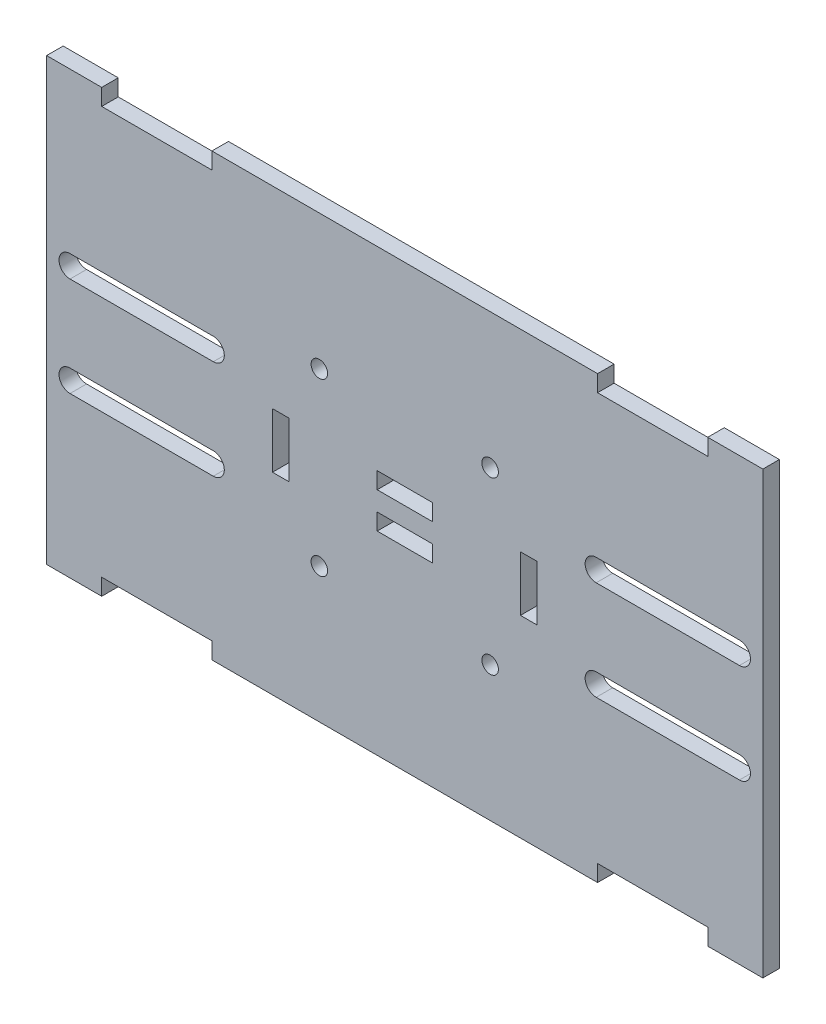
SolidWorks part; units mm, degrees
ref_plane "Front Plane" through (0, 0, 0) normal (0, 0, 1) x (1, 0, 0)
ref_plane "Top Plane" through (0, 0, 0) normal (0, 1, 0) x (1, 0, 0)
ref_plane "Right Plane" through (0, 0, 0) normal (1, 0, 0) x (0, 0, -1)
sketch "Sketch1" plane through (0, 0, 0) normal (0, 0, 1) x (1, 0, 0)
  line L0 (-55, 40) -> (-55, 37)
  line L1 (65, -40) -> (55, -40)
  line L2 (65, -40) -> (65, 40)
  line L3 (65, 40) -> (55, 40)
  line L4 (-65, -40) -> (-65, 40)
  line L5 (65, -40) -> (-65, 40) construction
  line L6 (65, 40) -> (-65, -40) construction
  line L7 (-55, 37) -> (-35, 37)
  line L8 (-35, 37) -> (-35, 40)
  line L9 (35, 40) -> (35, 37)
  line L10 (35, 37) -> (55, 37)
  line L11 (55, 37) -> (55, 40)
  line L12 (-55, -40) -> (-55, -37)
  line L13 (-55, -37) -> (-35, -37)
  line L14 (-35, -37) -> (-35, -40)
  line L15 (35, -40) -> (35, -37)
  line L16 (35, -37) -> (55, -37)
  line L17 (55, -37) -> (55, -40)
  line L18 (-55, 40) -> (-65, 40)
  line L19 (35, 40) -> (-35, 40)
  line L20 (35, -40) -> (-35, -40)
  line L21 (-55, -40) -> (-65, -40)
  line L22 (0, -40) -> (0, 40) construction
  line L23 (-65, 0) -> (65, 0) construction
  line L24 (21, -5) -> (24, -5)
  line L29 (-21, -5) -> (-24, -5)
  line L30 (-21, -5) -> (-21, 5)
  line L31 (-21, 5) -> (-24, 5)
  line L32 (-24, -5) -> (-24, 5)
  line L33 (-21, -5) -> (-24, 5) construction
  line L34 (-21, 5) -> (-24, -5) construction
  line L35 (24, -5) -> (24, 5)
  line L36 (21, 5) -> (24, 5)
  line L37 (21, -5) -> (21, 5)
  line L38 (-60.75, 11) -> (-34.75, 11)
  line L45 (-34.75, 7) -> (-60.75, 7)
  line L46 (-34.75, -7) -> (-60.75, -7)
  line L47 (-34.75, -11) -> (-60.75, -11)
  line L48 (34.75, 11) -> (60.75, 11)
  line L49 (60.75, 7) -> (34.75, 7)
  line L50 (34.75, -7) -> (60.75, -7)
  line L51 (60.75, -11) -> (34.75, -11)
  line L53 (5, 1.75) -> (-5, 1.75)
  line L54 (5, 1.75) -> (5, 4.75)
  line L55 (5, 4.75) -> (-5, 4.75)
  line L56 (-5, 1.75) -> (-5, 4.75)
  line L59 (5, -4.75) -> (-5, -4.75)
  line L60 (5, -1.75) -> (-5, -1.75)
  line L61 (-5, -1.75) -> (-5, -4.75)
  line L62 (5, -1.75) -> (5, -4.75)
  arc A0 (-60.75, 11) -> (-60.75, 7) centre (-60.75, 9) ccw
  arc A1 (-60.75, -11) -> (-60.75, -7) centre (-60.75, -9) cw
  arc A2 (-34.75, 7) -> (-34.75, 11) centre (-34.75, 9) ccw
  arc A3 (-34.75, -7) -> (-34.75, -11) centre (-34.75, -9) cw
  arc A4 (34.75, -7) -> (34.75, -11) centre (34.75, -9) ccw
  arc A5 (60.75, -11) -> (60.75, -7) centre (60.75, -9) ccw
  arc A6 (60.75, 11) -> (60.75, 7) centre (60.75, 9) cw
  arc A7 (34.75, 7) -> (34.75, 11) centre (34.75, 9) cw
  circle A8 centre (15.5, 15.5) radius 1.5
  circle A9 centre (-15.5, 15.5) radius 1.5
  circle A10 centre (15.5, -15.5) radius 1.5
  circle A11 centre (-15.5, -15.5) radius 1.5
  point P0 (0, 0)
  point P23 (36.5719, 15)
  point P26 (0, 25.5)
  point P27 (-22.5, 0)
  point P32 (0, 0)
  point P38 (0, 3.25)
  dimension "D13" = 4
  dimension "D16" = 4
  dimension "D19" = 3
  dimension "D1" = 130
  dimension "D2" = 10
  dimension "D3" = 3
  dimension "D4" = 20
  dimension "D5" = 10
  dimension "D6" = 80
  dimension "D7" = 10
  dimension "D8" = 10
  dimension "D9" = 20
  dimension "D10" = 3
  dimension "D11" = 10
  dimension "D12" = 18
  dimension "D14" = 60.75
  dimension "D15" = 26
  dimension "D17" = 31
  dimension "D18" = 31
  dimension "D20" = 10
  dimension "D21" = 3
  dimension "D22" = 3.5
extrude "Boss-Extrude1" add sketch "Sketch1" along normal blind 3
sketch "Sketch2" plane through (0, 0, 3) normal (0, 0, 1) x (1, 0, 0)
  line L0 (65, -40) -> (65, 40) construction
  line L7 (5, -1.75) -> (-5, -4.75) construction
  line L8 (5, 4.75) -> (-5, 4.75)
  line L9 (5, 4.75) -> (5, 1.75)
  line L10 (5, 1.75) -> (-5, 1.75)
  line L11 (-5, 4.75) -> (-5, 1.75)
  line L12 (5, 4.75) -> (-5, 1.75) construction
  line L13 (5, 1.75) -> (-5, 4.75) construction
  line L14 (5, -4.75) -> (-5, -1.75) construction
  line L15 (-5, -4.75) -> (-5, -1.75)
  line L16 (5, -1.75) -> (-5, -1.75)
  line L17 (5, -4.75) -> (5, -1.75)
  line L18 (5, -4.75) -> (-5, -4.75)
  point P12 (0, 3.25)
  point P22 (5, -3.25)
  dimension "D1" = 10
  dimension "D2" = 3
  dimension "D3" = 60
